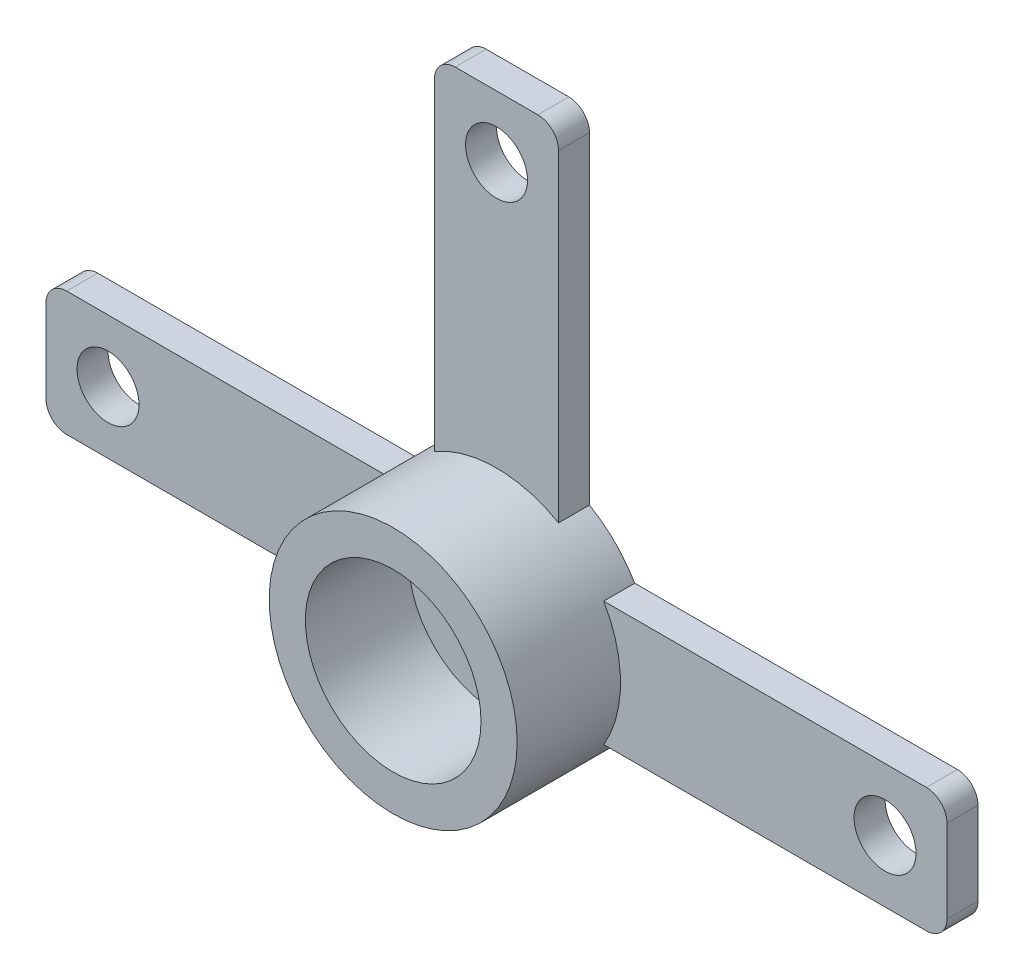
SolidWorks part; units mm, degrees
material "Thornel Mat VMA"
ref_plane "前视基准面" through (0, 0, 0) normal (0, 0, 1) x (1, 0, 0)
ref_plane "上视基准面" through (0, 0, 0) normal (0, 1, 0) x (1, 0, 0)
ref_plane "右视基准面" through (0, 0, 0) normal (1, 0, 0) x (0, 0, -1)
other "Configuration Table"
sketch "草图2" plane through (0, 0, 0) normal (0, 0, 1) x (1, 0, 0)
  line L0 (5.1884, -15.9867) -> (44, -15.9867) construction
  line L1 (-44, -22) -> (-5.1962, -22) construction
  line L2 (-44, -22) -> (-44, -15.9867) construction
  line L3 (-44, -15.9867) -> (-5.1884, -15.9867) construction
  line L4 (44, -22) -> (44, -15.9867) construction
  line L5 (5.1962, -22) -> (44, -22) construction
  line L6 (-5.1884, -15.9867) -> (-20.8, -15.9867)
  line L7 (-21.8, -16.9867) -> (-21.8, -21)
  line L8 (-20.8, -22) -> (-5.1962, -22)
  line L9 (5.1884, -15.9867) -> (20.8, -15.9867)
  line L10 (21.8, -16.9867) -> (21.8, -21)
  line L11 (20.8, -22) -> (5.1962, -22)
  line L13 (2, 2.8) -> (-2, 2.8)
  line L14 (3, 1.8) -> (3, -13.8038)
  line L16 (-3, 1.8) -> (-3, -13.8038)
  circle A0 centre (41, -19) radius 1.5 construction
  circle A1 centre (-41, -19) radius 1.5 construction
  arc A2 (-5.1962, -22) -> (5.1962, -22) centre (0, -19) ccw
  circle A3 centre (4.25, -19) radius 0.8 construction
  circle A4 centre (-4.25, -19) radius 0.8 construction
  arc A5 (5.1884, -15.9867) -> (3, -13.8038) centre (0, -19) ccw
  circle A6 centre (0, -14.75) radius 0.8 construction
  circle A7 centre (0, -23.25) radius 0.8 construction
  circle A8 centre (0, -19) radius 2.66
  circle A9 centre (-18.8, -19) radius 1.5
  circle A10 centre (18.8, -19) radius 1.5
  circle A11 centre (0, -0.2) radius 1.5
  arc A12 (-3, -13.8038) -> (-5.1884, -15.9867) centre (0, -19) ccw
  arc A13 (3, 1.8) -> (2, 2.8) centre (2, 1.8) ccw
  arc A14 (-3, 1.8) -> (-2, 2.8) centre (-2, 1.8) cw
  arc A15 (21.8, -21) -> (20.8, -22) centre (20.8, -21) cw
  arc A16 (21.8, -16.9867) -> (20.8, -15.9867) centre (20.8, -16.9867) ccw
  arc A17 (-21.8, -21) -> (-20.8, -22) centre (-20.8, -21) ccw
  arc A18 (-20.8, -15.9867) -> (-21.8, -16.9867) centre (-20.8, -16.9867) ccw
  point P22 (0, -19)
  point P46 (21.8, -22)
  point P49 (21.8, -15.9867)
  point P52 (-21.8, -22)
  point P55 (-21.8, -15.9867)
  dimension "D1" = 44
  dimension "D2" = 4.25
  dimension "D3" = 4.25
  dimension "D4" = 4.25
  dimension "D6" = 3
  dimension "D8" = 18.8
  dimension "D12" = 1
  dimension "D13" = 1
  dimension "D14" = 1
  dimension "D15" = 1
  dimension "D16" = 1
  dimension "D17" = 1
  dimension "D5" = 4.25
  dimension "D7" = 3
  dimension "D9" = 3
  dimension "D10" = 3
  dimension "D11" = 3
extrude "凸台-拉伸1" add sketch "草图2" along normal blind 1.5
sketch "草图3" plane through (0, 0, 1.5) normal (0, 0, 1) x (1, 0, 0)
  circle A0 centre (0, -19) radius 4.25
  circle A1 centre (0, -19) radius 6
extrude "凸台-拉伸2" add sketch "草图3" along normal blind 5
